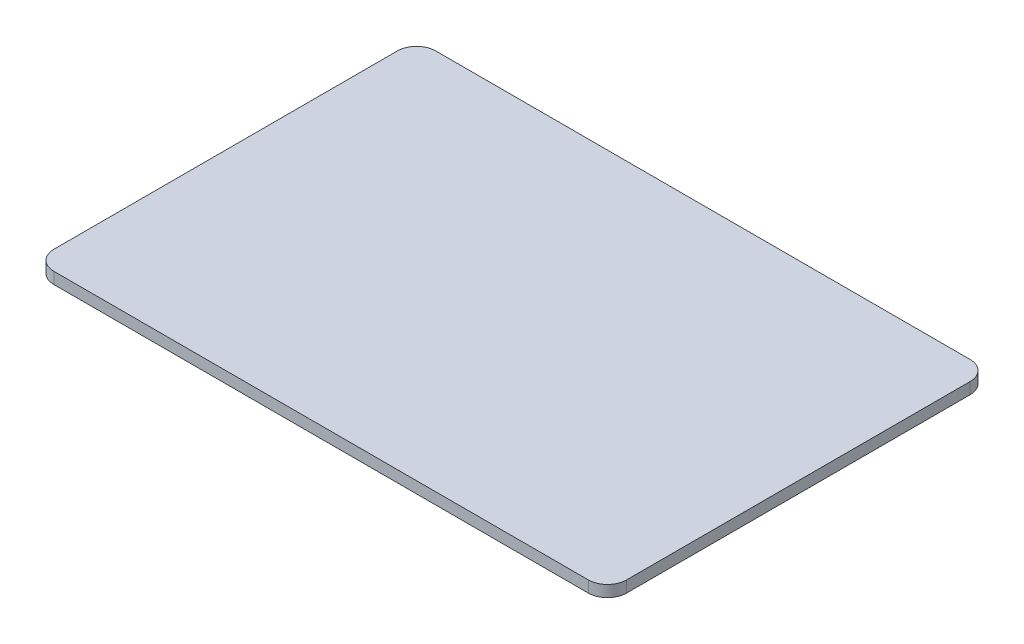
SolidWorks part; units mm, degrees
material "ABS PC"
ref_plane "Front Plane" through (0, 0, 0) normal (0, 0, 1) x (1, 0, 0)
ref_plane "Top Plane" through (0, 0, 0) normal (0, 1, 0) x (1, 0, 0)
ref_plane "Right Plane" through (0, 0, 0) normal (1, 0, 0) x (0, 0, -1)
sketch "Sketch1" plane through (0, 0, 0) normal (0, 1, 0) x (1, 0, 0)
  line L1 (-95.25, -63.5) -> (95.25, -63.5)
  line L2 (-95.25, -63.5) -> (-95.25, 63.5)
  line L3 (-95.25, 63.5) -> (95.25, 63.5)
  line L4 (95.25, -63.5) -> (95.25, 63.5)
  line L5 (-95.25, -63.5) -> (95.25, 63.5) construction
  line L6 (-95.25, 63.5) -> (95.25, -63.5) construction
  point P0 (0, 0)
  dimension "D1" = 190.5
  dimension "D2" = 127
extrude "Boss-Extrude1" add sketch "Sketch1" along normal blind 2.54 and the other way blind 1.27
fillet "Fillet1" radius 6.35 4 edges at (95.25, 0.635, -63.5) (95.25, 0.635, 63.5) (-95.25, 0.635, 63.5) (-95.25, 0.635, -63.5)
